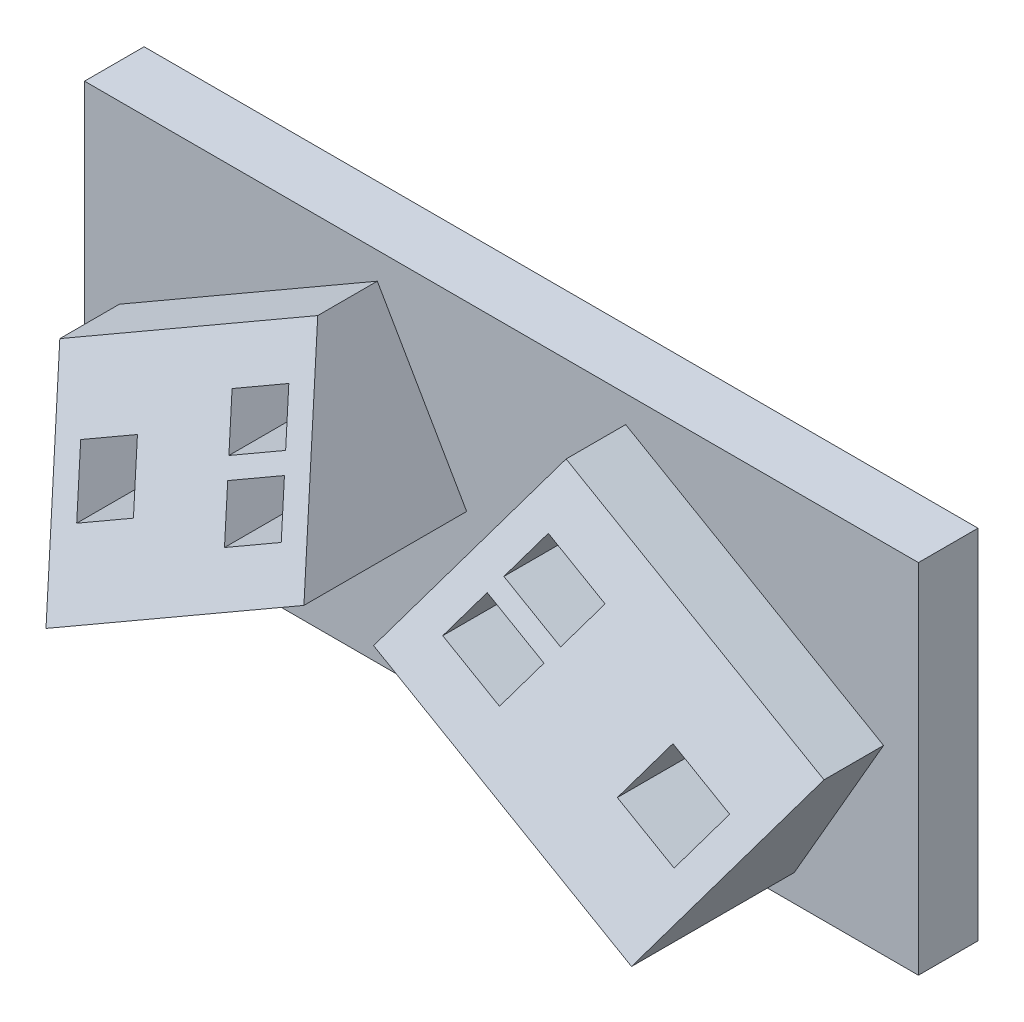
SolidWorks part; units mm, degrees
ref_plane "Front Plane" through (0, 0, 0) normal (0, 0, 1) x (1, 0, 0)
ref_plane "Top Plane" through (0, 0, 0) normal (0, 1, 0) x (1, 0, 0)
ref_plane "Right Plane" through (0, 0, 0) normal (1, 0, 0) x (0, 0, -1)
sketch "Sketch1" plane through (0, 0, 0) normal (0, 0, 1) x (1, 0, 0)
  line L1 (-35.9801, 23.4693) -> (-21.9801, 23.4693)
  line L2 (-35.9801, 23.4693) -> (-35.9801, 17.4693)
  line L3 (-35.9801, 17.4693) -> (-21.9801, 17.4693)
  line L4 (-21.9801, 23.4693) -> (-21.9801, 17.4693)
  dimension "D1" = 6
  dimension "D2" = 14
extrude "Boss-Extrude1" add sketch "Sketch1" along normal blind 1
sketch3d "3DSketch3"
  line L0 (-35.9801, 23.4693, 1) -> (-35.9801, 17.4693, 1) construction
  line L1 (-35.3952, 20.5183, 1) -> (-31.065, 23.0183, 1)
  line L2 (-35.3952, 20.5183, 1) -> (-33.8952, 17.9202, 1)
  line L3 (-33.8952, 17.9202, 1) -> (-29.565, 20.4202, 1)
  line L4 (-31.065, 23.0183, 1) -> (-29.565, 20.4202, 1)
  line L5 (-35.3952, 20.5183, 1) -> (-29.565, 20.4202, 1) construction
  line L6 (-33.8952, 17.9202, 1) -> (-31.065, 23.0183, 1) construction
  line L7 (-21.9801, 23.4693, 1) -> (-35.9801, 23.4693, 1) construction
  point P0 (-32.4801, 20.4693, 1)
  point P5 (0, 0, 0)
  point P6 (0, 0, 0)
  point P7 (0, 0, 0)
  dimension "D1" = 3
  dimension "D2" = 5
  dimension "D3" = 1.5
  dimension "D4" = 2.5
  dimension "D5" = 2.5
  dimension "D6" = 1.5
  dimension "D7" = 3.5
  dimension "D8" = 3
extrude "Boss-Extrude2" add sketch "3DSketch3" along direction (0, 0, 1) on the side against the normal blind 10
sketch "Sketch5" plane through (-17.6617, -10.197, 0) normal (-0.866, -0.5, 0) x (0, 0, 1)
  line L0 (1, 32.467) -> (11, 32.467) construction
  line L1 (11, 32.467) -> (11, 35.467) construction
  line L2 (1, 35.467) -> (11, 35.467) construction
  line L3 (3.7321, 32.467) -> (11, 32.467)
  line L4 (11, 32.467) -> (11, 35.467)
  line L5 (2, 35.467) -> (11, 35.467)
  line L6 (2, 35.467) -> (3.7321, 32.467)
  dimension "D1" = 60
  dimension "D2" = 9
extrude "Cut-Extrude1" cut sketch "Sketch5" against normal up to surface (5 mm away) up to face at (-30.69, 22.3688, 3.5)
ref_plane "Plane1" through (-28.9801, 0, 0) normal (-1, 0, 0) x (0, 0, 1)
sketch "Sketch8" plane through (-4.8664, 8.4288, 16.8576) normal (-0.25, 0.433, 0.866) x (0.9682, 0.1118, 0.2236)
  line L0 (-26.2823, 17.0247) -> (-29.8601, 15.2358)
  line L1 (-26.2823, 17.0247) -> (-27.1768, 18.8136)
  line L2 (-29.8601, 15.2358) -> (-30.7545, 17.0247)
  line L3 (-27.1768, 18.8136) -> (-30.7545, 17.0247)
  line L4 (-25.5087, 16.5954) -> (-27.0579, 19.6938) construction
  line L5 (-25.5087, 16.5954) -> (-29.9808, 14.3593) construction
  line L6 (-27.2886, 16.5775) -> (-27.6464, 17.293)
  line L7 (-27.2886, 16.5775) -> (-26.3047, 17.0694)
  line L8 (-27.6464, 17.293) -> (-26.6625, 17.785)
  line L9 (-27.7805, 17.5614) -> (-28.1383, 18.2769)
  line L10 (-27.7805, 17.5614) -> (-26.7966, 18.0533)
  line L11 (-28.1383, 18.2769) -> (-27.1544, 18.7688)
  line L12 (-30.0837, 15.6831) -> (-29.0998, 16.175)
  line L13 (-29.0998, 16.175) -> (-29.547, 17.0694)
  line L14 (-29.547, 17.0694) -> (-30.5309, 16.5775)
  point P20 (-30.3073, 16.1303)
  dimension "D1" = 4
  dimension "D2" = 2
  dimension "D3" = 0.5
  dimension "D4" = 0.73
  dimension "D5" = 4
  dimension "D6" = 2
  dimension "D7" = 0.8
  dimension "D8" = 1.1
  dimension "D9" = 0.05
  dimension "D10" = 0.05
  dimension "D11" = 0.5
  dimension "D12" = 1
extrude "Cut-Extrude4" cut sketch "Sketch8" along direction (0, 0, 1) on the side against the normal mid plane 10 contours L11 L9 L10 L1 | L8 L6 L7 L1 | L13 L14 L2 L12
mirror "Mirror1" about plane through (-28.9801, 0, 0) normal (-1, 0, 0) of "Cut-Extrude4", "Cut-Extrude1", "Boss-Extrude2"
